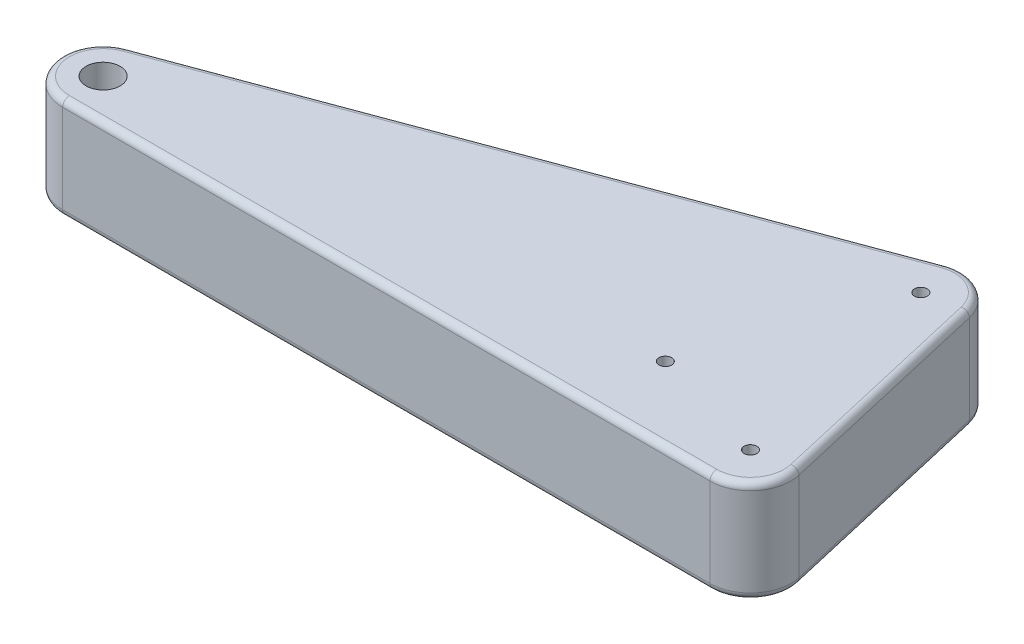
SolidWorks part; units mm, degrees
material "ABS"
ref_plane "Front Plane" through (0, 0, 0) normal (0, 0, 1) x (1, 0, 0)
ref_plane "Top Plane" through (0, 0, 0) normal (0, 1, 0) x (1, 0, 0)
ref_plane "Right Plane" through (0, 0, 0) normal (1, 0, 0) x (0, 0, -1)
sketch "Sketch1" plane through (0, 0, 0) normal (0, 1, 0) x (1, 0, 0)
  line L0 (0, 0) -> (2.3812, 0) construction
  line L1 (241.3, 0) -> (241.3, 15.0813) construction
  line L2 (241.3, 82.55) -> (237.3312, 82.55) construction
  line L3 (-5.2511, 14.1375) -> (216.9989, 96.6875)
  line L4 (236.945, 85.9412) -> (255.995, 3.3912)
  line L5 (0, -15.0813) -> (241.3, -15.0813)
  line L6 (238.9187, 0) -> (241.3, 0) construction
  line L7 (241.3, 67.0697) -> (241.3, 82.55) construction
  line L8 (224.6312, 82.55) -> (222.25, 82.55) construction
  circle A0 centre (0, 0) radius 2.3813
  arc A1 (-5.2511, 14.1375) -> (0, -15.0813) centre (0, 0) ccw
  circle A2 centre (241.3, 0) radius 2.3813
  arc A3 (241.3, -15.0813) -> (255.995, 3.3912) centre (241.3, 0) ccw
  circle A4 centre (222.25, 82.55) radius 2.3813
  arc A5 (237.3312, 82.55) -> (216.9989, 96.6875) centre (222.25, 82.55) ccw
  circle A6 centre (196.85, 12.7) radius 2.3813
  circle A7 centre (241.3, 0) radius 2.3813
  dimension "D1" = 4.7625
  dimension "D2" = 30.1625
  dimension "D4" = 4.7625
  dimension "D5" = 30.1625
  dimension "D8" = 4.7625
  dimension "D9" = 30.1625
  dimension "D12" = 4.7625
  dimension "D14" = 4.7625
  dimension "D3" = 241.3
  dimension "D6" = 82.55
  dimension "D7" = 19.05
  dimension "D10" = 44.45
  dimension "D11" = 12.7
  dimension "D13" = 241.3
extrude "Boss-Extrude1" add sketch "Sketch1" along normal blind 38.1
fillet "Fillet1" radius 2.54 12 edges at (120.65, 0, 15.0813) (-14.8434, 0, 2.6676) (105.8739, 0, -55.4125) (229.4032, 0, -95.8269) (246.47, 0, -44.6662) (120.65, 38.1, 15.0813) (-14.8434, 38.1, 2.6676) (105.8739, 38.1, -55.4125) (229.4032, 38.1, -95.8269) (246.47, 38.1, -44.6662) (253.1023, 0, 9.3889) (253.1023, 38.1, 9.3889)
sketch "Sketch2" plane through (0, 38.1, 0) normal (0, 1, 0) x (1, 0, 0)
  circle A0 centre (0, 0) radius 6.35
  dimension "D1" = 12.7
extrude "Cut-Extrude1" cut sketch "Sketch2" against normal blind 19.05
